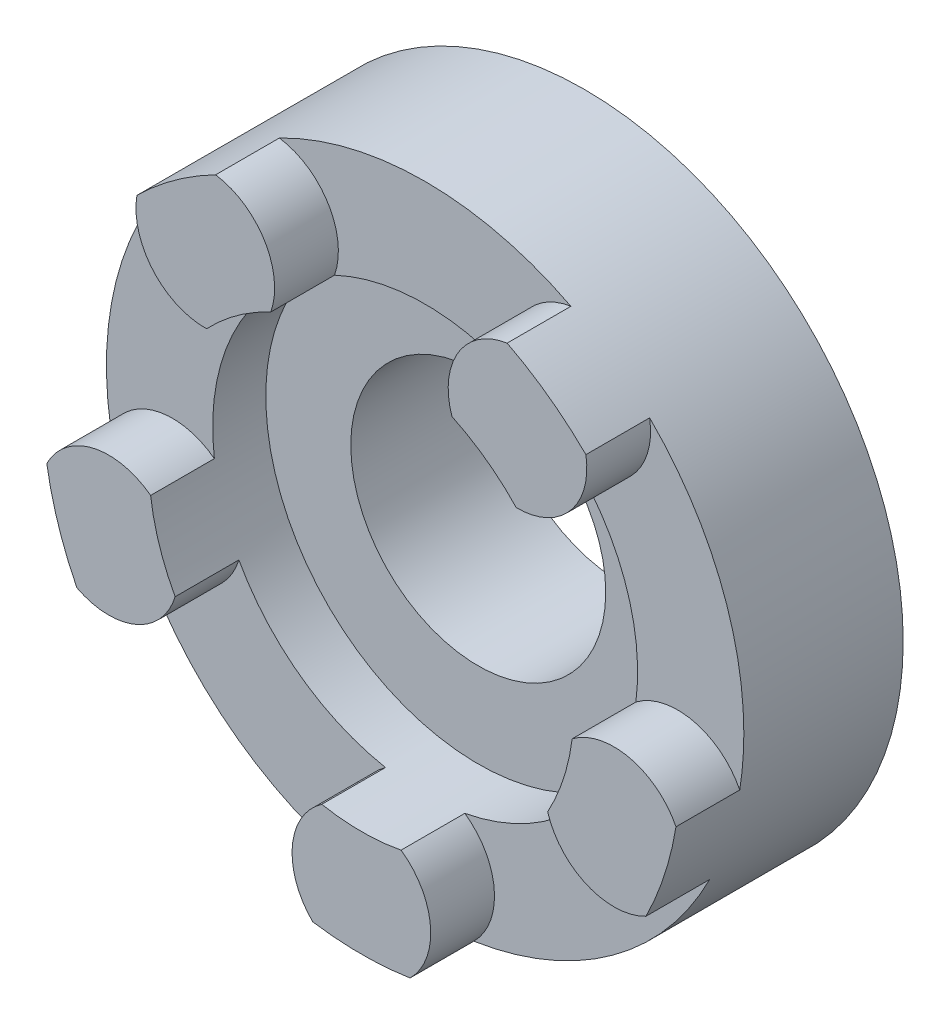
SolidWorks part; units mm, degrees
ref_plane "Front Plane" through (0, 0, 0) normal (0, 0, 1) x (1, 0, 0)
ref_plane "Top Plane" through (0, 0, 0) normal (0, 1, 0) x (1, 0, 0)
ref_plane "Right Plane" through (0, 0, 0) normal (1, 0, 0) x (0, 0, -1)
sketch "Sketch1" plane through (0, 0, 0) normal (0, 0, 1) x (1, 0, 0)
  circle A0 centre (0, 0) radius 10
  circle A1 centre (0, 0) radius 15
  circle A2 centre (0, 0) radius 6
extrude "Boss-Extrude1" add sketch "Sketch1" against normal blind 5 contours A1 A0 | A0 A2
sketch "Sketch2" plane through (0, 0, 0) normal (0, 0, 1) x (1, 0, 0)
  circle A0 centre (0, 0) radius 10
  circle A1 centre (0, 0) radius 15
extrude "Boss-Extrude2" add sketch "Sketch2" along normal blind 2.5
sketch "Sketch3" plane through (0, 0, 2.5) normal (0, 0, 1) x (1, 0, 0)
  line L0 (0, 0) -> (0, -15) construction
  circle A0 centre (0, 0) radius 15 construction
  arc A1 (-2.2906, -14.8241) -> (2.2906, -14.8241) centre (0, 0) ccw
  arc A2 (-1.8675, -9.8241) -> (1.8675, -9.8241) centre (0, 0) ccw
  arc A5 (3.2352, -12.0741) -> (2.2906, -14.8241) centre (0, -12.5) cw
  arc A6 (3.2352, -12.0741) -> (1.8675, -9.8241) centre (0, -12.5) ccw
  arc A7 (-3.2352, -12.0741) -> (-2.2906, -14.8241) centre (0, -12.5) ccw
  arc A8 (-3.2352, -12.0741) -> (-1.8675, -9.8241) centre (0, -12.5) cw
  arc A37 (-14.8064, -2.4024) -> (-13.3907, -6.7594) centre (0, 0) ccw
  arc A38 (-9.9203, -1.2597) -> (-8.7662, -4.8119) centre (0, 0) ccw
  arc A39 (-10.4834, -6.808) -> (-13.3907, -6.7594) centre (-11.8882, -3.8627) cw
  arc A40 (-10.4834, -6.808) -> (-8.7662, -4.8119) centre (-11.8882, -3.8627) ccw
  arc A41 (-12.4829, -0.6542) -> (-14.8064, -2.4024) centre (-11.8882, -3.8627) ccw
  arc A42 (-12.4829, -0.6542) -> (-9.9203, -1.2597) centre (-11.8882, -3.8627) cw
  arc A43 (-6.8602, 13.3393) -> (-10.5665, 10.6465) centre (0, 0) ccw
  arc A44 (-4.2636, 9.0455) -> (-7.2853, 6.8501) centre (0, 0) ccw
  arc A45 (-9.7143, 7.8665) -> (-10.5665, 10.6465) centre (-7.3473, 10.1127) cw
  arc A46 (-9.7143, 7.8665) -> (-7.2853, 6.8501) centre (-7.3473, 10.1127) ccw
  arc A47 (-4.4796, 11.6698) -> (-6.8602, 13.3393) centre (-7.3473, 10.1127) ccw
  arc A48 (-4.4796, 11.6698) -> (-4.2636, 9.0455) centre (-7.3473, 10.1127) cw
  arc A49 (10.5665, 10.6465) -> (6.8602, 13.3393) centre (0, 0) ccw
  arc A50 (7.2853, 6.8501) -> (4.2636, 9.0455) centre (0, 0) ccw
  arc A51 (4.4796, 11.6698) -> (6.8602, 13.3393) centre (7.3473, 10.1127) cw
  arc A52 (4.4796, 11.6698) -> (4.2636, 9.0455) centre (7.3473, 10.1127) ccw
  arc A53 (9.7143, 7.8665) -> (10.5665, 10.6465) centre (7.3473, 10.1127) ccw
  arc A54 (9.7143, 7.8665) -> (7.2853, 6.8501) centre (7.3473, 10.1127) cw
  arc A55 (13.3907, -6.7594) -> (14.8064, -2.4024) centre (0, 0) ccw
  arc A56 (8.7662, -4.8119) -> (9.9203, -1.2597) centre (0, 0) ccw
  arc A57 (12.4829, -0.6542) -> (14.8064, -2.4024) centre (11.8882, -3.8627) cw
  arc A58 (12.4829, -0.6542) -> (9.9203, -1.2597) centre (11.8882, -3.8627) ccw
  arc A59 (10.4834, -6.808) -> (13.3907, -6.7594) centre (11.8882, -3.8627) ccw
  arc A60 (10.4834, -6.808) -> (8.7662, -4.8119) centre (11.8882, -3.8627) cw
  point P12 (3.2352, -12.0741)
  point P15 (-3.2352, -12.0741)
  point P21 (-10.4834, -6.808)
  point P24 (-12.4829, -0.6542)
  point P31 (-9.7143, 7.8665)
  point P33 (-4.4796, 11.6698)
  point P40 (4.4796, 11.6698)
  point P42 (9.7143, 7.8665)
  point P49 (12.4829, -0.6542)
  point P51 (10.4834, -6.808)
  dimension "D1" = 5
extrude "Boss-Extrude4" add sketch "Sketch3" along normal blind 3
sketch "Sketch4" plane through (0, 0, -5) normal (0, 0, -1) x (-1, 0, 0)
  circle A3 centre (0, 0) radius 6
  circle A4 centre (0, 0) radius 6 construction
  circle A5 centre (0, 0) radius 7
  dimension "D1" = 1
extrude "Boss-Extrude5" add sketch "Sketch4" along normal blind 1.75
